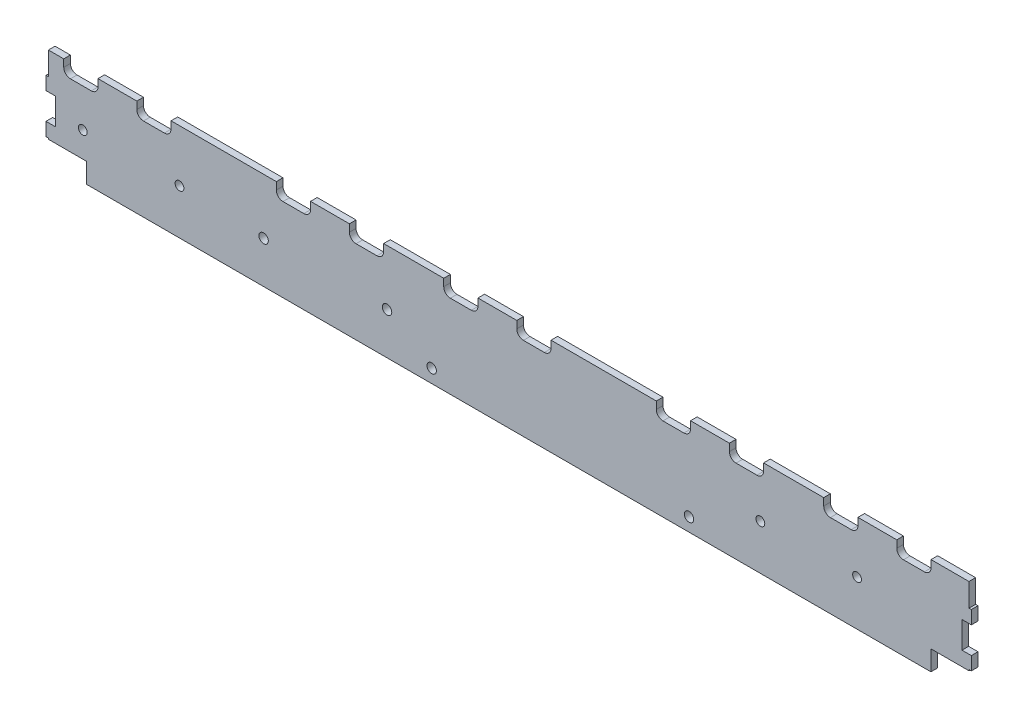
SolidWorks part; units mm, degrees
material "PP Film"
ref_plane "X-Y Datum" through (0, 0, 0) normal (0, 0, 1) x (1, 0, 0)
ref_plane "X-Z Datum" through (0, 0, 0) normal (0, 1, 0) x (1, 0, 0)
ref_plane "Y-Z Datum" through (0, 0, 0) normal (1, 0, 0) x (0, 0, -1)
sketch "Sketch2" plane through (0, 0, 0) normal (0, 0, 1) x (1, 0, 0)
  line L0 (-166.3768, -167.122) -> (-166.3768, -157.216)
  line L1 (-167.5198, -174.615) -> (-167.5198, -187.315)
  line L2 (273.6032, -167.122) -> (273.6032, -157.216)
  line L3 (-163.0588, -174.615) -> (-163.0588, -187.315)
  line L4 (274.7462, -174.615) -> (274.7462, -187.315)
  line L5 (270.2852, -174.615) -> (270.2852, -187.315)
  line L64 (255.4262, -203.714) -> (255.4262, -194.181)
  line L65 (255.4262, -194.181) -> (273.6032, -194.181)
  line L66 (275.7462, -167.122) -> (275.7462, -157.216)
  line L67 (255.4262, -194.181) -> (273.6032, -194.181)
  line L68 (273.6032, -194.181) -> (273.6032, -193.665)
  line L69 (273.6032, -193.665) -> (274.7462, -193.665)
  line L70 (274.7462, -193.665) -> (274.7462, -187.315)
  line L71 (274.7462, -168.265) -> (273.6032, -168.265)
  line L72 (273.6032, -168.265) -> (273.6032, -167.122)
  line L73 (273.6032, -167.122) -> (275.7462, -167.122)
  line L74 (-166.3768, -194.181) -> (-148.1998, -194.181)
  line L75 (275.7462, -157.216) -> (255.4633, -157.216)
  line L76 (255.4633, -157.216) -> (255.4633, -160.708)
  line L77 (252.2883, -163.883) -> (242.2883, -163.883)
  line L78 (239.1133, -160.708) -> (239.1133, -157.216)
  line L79 (239.1133, -157.216) -> (220.5383, -157.216)
  line L80 (220.5383, -157.216) -> (220.5383, -160.708)
  line L81 (217.3633, -163.883) -> (207.3633, -163.883)
  line L82 (204.1883, -160.708) -> (204.1883, -157.216)
  line L83 (204.1883, -157.216) -> (175.4521, -157.216)
  line L84 (175.4521, -157.216) -> (175.4521, -160.708)
  line L85 (172.2771, -163.883) -> (162.2771, -163.883)
  line L86 (159.1021, -160.708) -> (159.1021, -157.216)
  line L87 (159.1021, -157.216) -> (140.5271, -157.216)
  line L88 (140.5271, -157.216) -> (140.5271, -160.708)
  line L89 (137.3521, -163.883) -> (127.3521, -163.883)
  line L90 (124.1771, -160.708) -> (124.1771, -157.216)
  line L91 (124.1771, -157.216) -> (73.8493, -157.216)
  line L92 (73.8493, -157.216) -> (73.8493, -160.708)
  line L93 (70.6743, -163.883) -> (60.6743, -163.883)
  line L94 (57.4993, -160.708) -> (57.4993, -157.216)
  line L95 (57.4993, -157.216) -> (38.9243, -157.216)
  line L96 (38.9243, -157.216) -> (38.9243, -160.708)
  line L97 (35.7493, -163.883) -> (25.7493, -163.883)
  line L98 (22.5743, -160.708) -> (22.5743, -157.216)
  line L99 (22.5743, -157.216) -> (-6.1619, -157.216)
  line L100 (-6.1619, -157.216) -> (-6.1619, -160.708)
  line L101 (-9.3369, -163.883) -> (-19.3369, -163.883)
  line L102 (-22.5119, -160.708) -> (-22.5119, -157.216)
  line L103 (-22.5119, -157.216) -> (-41.0869, -157.216)
  line L104 (-41.0869, -157.216) -> (-41.0869, -160.708)
  line L105 (-44.2619, -163.883) -> (-54.2619, -163.883)
  line L106 (-57.4369, -160.708) -> (-57.4369, -157.216)
  line L107 (-57.4369, -157.216) -> (-107.7647, -157.216)
  line L108 (-107.7647, -157.216) -> (-107.7647, -160.708)
  line L109 (-110.9397, -163.883) -> (-120.9397, -163.883)
  line L110 (-124.1147, -160.708) -> (-124.1147, -157.216)
  line L111 (-124.1147, -157.216) -> (-142.6897, -157.216)
  line L112 (-142.6897, -157.216) -> (-142.6897, -160.708)
  line L113 (-145.8647, -163.883) -> (-155.8647, -163.883)
  line L114 (-159.0397, -160.708) -> (-159.0397, -157.216)
  line L115 (-159.0397, -157.216) -> (-168.5198, -157.216)
  line L116 (-168.5198, -157.216) -> (-168.5198, -167.122)
  line L117 (-168.5198, -167.122) -> (-166.3768, -167.122)
  line L118 (-166.3768, -167.122) -> (-166.3768, -168.265)
  line L119 (-166.3768, -168.265) -> (-167.5198, -168.265)
  line L120 (-167.5198, -168.265) -> (-167.5198, -174.615)
  line L121 (-167.5198, -193.665) -> (-166.3768, -193.665)
  line L122 (-166.3768, -193.665) -> (-166.3768, -194.181)
  line L123 (-166.3768, -194.181) -> (-148.1998, -194.181)
  line L126 (-148.1998, -194.181) -> (-148.1998, -203.714)
  line L127 (-148.1998, -203.714) -> (255.4262, -203.714)
  line L128 (255.4262, -203.714) -> (255.4262, -194.181)
  line L130 (275.7462, -167.122) -> (275.7462, -157.216)
  line L132 (273.6032, -194.181) -> (273.6032, -193.665)
  line L133 (273.6032, -193.665) -> (274.7462, -193.665)
  line L134 (274.7462, -193.665) -> (274.7462, -187.315)
  line L135 (274.7462, -168.265) -> (273.6032, -168.265)
  line L136 (273.6032, -168.265) -> (273.6032, -167.122)
  line L137 (273.6032, -167.122) -> (275.7462, -167.122)
  line L139 (275.7462, -157.216) -> (255.4633, -157.216)
  line L140 (255.4633, -157.216) -> (255.4633, -160.708)
  line L141 (252.2883, -163.883) -> (242.2883, -163.883)
  line L142 (239.1133, -160.708) -> (239.1133, -157.216)
  line L143 (239.1133, -157.216) -> (220.5383, -157.216)
  line L144 (220.5383, -157.216) -> (220.5383, -160.708)
  line L145 (217.3633, -163.883) -> (207.3633, -163.883)
  line L146 (204.1883, -160.708) -> (204.1883, -157.216)
  line L147 (204.1883, -157.216) -> (175.4521, -157.216)
  line L148 (175.4521, -157.216) -> (175.4521, -160.708)
  line L149 (172.2771, -163.883) -> (162.2771, -163.883)
  line L150 (159.1021, -160.708) -> (159.1021, -157.216)
  line L151 (159.1021, -157.216) -> (140.5271, -157.216)
  line L152 (140.5271, -157.216) -> (140.5271, -160.708)
  line L153 (137.3521, -163.883) -> (127.3521, -163.883)
  line L154 (124.1771, -160.708) -> (124.1771, -157.216)
  line L155 (124.1771, -157.216) -> (73.8493, -157.216)
  line L156 (73.8493, -157.216) -> (73.8493, -160.708)
  line L157 (70.6743, -163.883) -> (60.6743, -163.883)
  line L158 (57.4993, -160.708) -> (57.4993, -157.216)
  line L159 (57.4993, -157.216) -> (38.9243, -157.216)
  line L160 (38.9243, -157.216) -> (38.9243, -160.708)
  line L161 (35.7493, -163.883) -> (25.7493, -163.883)
  line L162 (22.5743, -160.708) -> (22.5743, -157.216)
  line L163 (22.5743, -157.216) -> (-6.1619, -157.216)
  line L164 (-6.1619, -157.216) -> (-6.1619, -160.708)
  line L165 (-9.3369, -163.883) -> (-19.3369, -163.883)
  line L166 (-22.5119, -160.708) -> (-22.5119, -157.216)
  line L167 (-22.5119, -157.216) -> (-41.0869, -157.216)
  line L168 (-41.0869, -157.216) -> (-41.0869, -160.708)
  line L169 (-44.2619, -163.883) -> (-54.2619, -163.883)
  line L170 (-57.4369, -160.708) -> (-57.4369, -157.216)
  line L171 (-57.4369, -157.216) -> (-107.7647, -157.216)
  line L172 (-107.7647, -157.216) -> (-107.7647, -160.708)
  line L173 (-110.9397, -163.883) -> (-120.9397, -163.883)
  line L174 (-124.1147, -160.708) -> (-124.1147, -157.216)
  line L175 (-124.1147, -157.216) -> (-142.6897, -157.216)
  line L176 (-142.6897, -157.216) -> (-142.6897, -160.708)
  line L177 (-145.8647, -163.883) -> (-155.8647, -163.883)
  line L178 (-159.0397, -160.708) -> (-159.0397, -157.216)
  line L179 (-159.0397, -157.216) -> (-168.5198, -157.216)
  line L180 (-168.5198, -157.216) -> (-168.5198, -167.122)
  line L181 (-168.5198, -167.122) -> (-166.3768, -167.122)
  line L182 (-166.3768, -167.122) -> (-166.3768, -168.265)
  line L183 (-166.3768, -168.265) -> (-167.5198, -168.265)
  line L184 (-167.5198, -168.265) -> (-167.5198, -174.615)
  line L185 (-167.5198, -193.665) -> (-166.3768, -193.665)
  line L186 (-166.3768, -193.665) -> (-166.3768, -194.181)
  line L190 (-148.1998, -194.181) -> (-148.1998, -203.714)
  line L191 (-148.1998, -203.714) -> (255.4262, -203.714)
  line L249 (255.4262, -194.181) -> (273.6032, -194.181)
  line L250 (273.6032, -194.181) -> (273.6032, -193.665)
  line L251 (273.6032, -193.665) -> (274.7462, -193.665)
  line L252 (274.7462, -193.665) -> (274.7462, -187.315)
  line L253 (274.7462, -168.265) -> (273.6032, -168.265)
  line L254 (273.6032, -168.265) -> (273.6032, -167.122)
  line L255 (273.6032, -167.122) -> (275.7462, -167.122)
  line L256 (275.7462, -167.122) -> (275.7462, -157.216)
  line L257 (275.7462, -157.216) -> (255.4633, -157.216)
  line L258 (255.4633, -157.216) -> (255.4633, -160.708)
  line L259 (252.2883, -163.883) -> (242.2883, -163.883)
  line L260 (239.1133, -160.708) -> (239.1133, -157.216)
  line L261 (239.1133, -157.216) -> (220.5383, -157.216)
  line L262 (220.5383, -157.216) -> (220.5383, -160.708)
  line L263 (217.3633, -163.883) -> (207.3633, -163.883)
  line L264 (204.1883, -160.708) -> (204.1883, -157.216)
  line L265 (204.1883, -157.216) -> (175.4521, -157.216)
  line L266 (175.4521, -157.216) -> (175.4521, -160.708)
  line L267 (172.2771, -163.883) -> (162.2771, -163.883)
  line L268 (159.1021, -160.708) -> (159.1021, -157.216)
  line L269 (159.1021, -157.216) -> (140.5271, -157.216)
  line L270 (140.5271, -157.216) -> (140.5271, -160.708)
  line L271 (137.3521, -163.883) -> (127.3521, -163.883)
  line L272 (124.1771, -160.708) -> (124.1771, -157.216)
  line L273 (124.1771, -157.216) -> (73.8493, -157.216)
  line L274 (73.8493, -157.216) -> (73.8493, -160.708)
  line L275 (70.6743, -163.883) -> (60.6743, -163.883)
  line L276 (57.4993, -160.708) -> (57.4993, -157.216)
  line L277 (57.4993, -157.216) -> (38.9243, -157.216)
  line L278 (38.9243, -157.216) -> (38.9243, -160.708)
  line L279 (35.7493, -163.883) -> (25.7493, -163.883)
  line L280 (22.5743, -160.708) -> (22.5743, -157.216)
  line L281 (22.5743, -157.216) -> (-6.1619, -157.216)
  line L282 (-6.1619, -157.216) -> (-6.1619, -160.708)
  line L283 (-9.3369, -163.883) -> (-19.3369, -163.883)
  line L284 (-22.5119, -160.708) -> (-22.5119, -157.216)
  line L285 (-22.5119, -157.216) -> (-41.0869, -157.216)
  line L286 (-41.0869, -157.216) -> (-41.0869, -160.708)
  line L287 (-44.2619, -163.883) -> (-54.2619, -163.883)
  line L288 (-57.4369, -160.708) -> (-57.4369, -157.216)
  line L289 (-57.4369, -157.216) -> (-107.7647, -157.216)
  line L290 (-107.7647, -157.216) -> (-107.7647, -160.708)
  line L291 (-110.9397, -163.883) -> (-120.9397, -163.883)
  line L292 (-124.1147, -160.708) -> (-124.1147, -157.216)
  line L293 (-124.1147, -157.216) -> (-142.6897, -157.216)
  line L294 (-142.6897, -157.216) -> (-142.6897, -160.708)
  line L295 (-145.8647, -163.883) -> (-155.8647, -163.883)
  line L296 (-159.0397, -160.708) -> (-159.0397, -157.216)
  line L297 (-159.0397, -157.216) -> (-168.5198, -157.216)
  line L298 (-168.5198, -157.216) -> (-168.5198, -167.122)
  line L299 (-168.5198, -167.122) -> (-166.3768, -167.122)
  line L300 (-166.3768, -167.122) -> (-166.3768, -168.265)
  line L301 (-166.3768, -168.265) -> (-167.5198, -168.265)
  line L302 (-167.5198, -168.265) -> (-167.5198, -174.615)
  line L303 (-167.5198, -193.665) -> (-166.3768, -193.665)
  line L304 (-166.3768, -193.665) -> (-166.3768, -194.181)
  line L305 (-166.3768, -194.181) -> (-148.1998, -194.181)
  line L306 (-148.1998, -194.181) -> (-148.1998, -203.714)
  line L307 (-148.1998, -203.714) -> (255.4262, -203.714)
  line L308 (255.4262, -203.714) -> (255.4262, -194.181)
  line L309 (255.4262, -194.181) -> (273.6032, -194.181)
  line L310 (273.6032, -194.181) -> (273.6032, -193.665)
  line L311 (273.6032, -193.665) -> (274.7462, -193.665)
  line L312 (274.7462, -193.665) -> (274.7462, -187.315)
  line L313 (274.7462, -168.265) -> (273.6032, -168.265)
  line L314 (273.6032, -168.265) -> (273.6032, -167.122)
  line L315 (273.6032, -167.122) -> (275.7462, -167.122)
  line L316 (275.7462, -167.122) -> (275.7462, -157.216)
  line L317 (275.7462, -157.216) -> (255.4633, -157.216)
  line L318 (255.4633, -157.216) -> (255.4633, -160.708)
  line L319 (252.2883, -163.883) -> (242.2883, -163.883)
  line L320 (239.1133, -160.708) -> (239.1133, -157.216)
  line L321 (239.1133, -157.216) -> (220.5383, -157.216)
  line L322 (220.5383, -157.216) -> (220.5383, -160.708)
  line L323 (217.3633, -163.883) -> (207.3633, -163.883)
  line L324 (204.1883, -160.708) -> (204.1883, -157.216)
  line L325 (204.1883, -157.216) -> (175.4521, -157.216)
  line L326 (175.4521, -157.216) -> (175.4521, -160.708)
  line L327 (172.2771, -163.883) -> (162.2771, -163.883)
  line L328 (159.1021, -160.708) -> (159.1021, -157.216)
  line L329 (159.1021, -157.216) -> (140.5271, -157.216)
  line L330 (140.5271, -157.216) -> (140.5271, -160.708)
  line L331 (137.3521, -163.883) -> (127.3521, -163.883)
  line L332 (124.1771, -160.708) -> (124.1771, -157.216)
  line L333 (124.1771, -157.216) -> (73.8493, -157.216)
  line L334 (73.8493, -157.216) -> (73.8493, -160.708)
  line L335 (70.6743, -163.883) -> (60.6743, -163.883)
  line L336 (57.4993, -160.708) -> (57.4993, -157.216)
  line L337 (57.4993, -157.216) -> (38.9243, -157.216)
  line L338 (38.9243, -157.216) -> (38.9243, -160.708)
  line L339 (35.7493, -163.883) -> (25.7493, -163.883)
  line L340 (22.5743, -160.708) -> (22.5743, -157.216)
  line L341 (22.5743, -157.216) -> (-6.1619, -157.216)
  line L342 (-6.1619, -157.216) -> (-6.1619, -160.708)
  line L343 (-9.3369, -163.883) -> (-19.3369, -163.883)
  line L344 (-22.5119, -160.708) -> (-22.5119, -157.216)
  line L345 (-22.5119, -157.216) -> (-41.0869, -157.216)
  line L346 (-41.0869, -157.216) -> (-41.0869, -160.708)
  line L347 (-44.2619, -163.883) -> (-54.2619, -163.883)
  line L348 (-57.4369, -160.708) -> (-57.4369, -157.216)
  line L349 (-57.4369, -157.216) -> (-107.7647, -157.216)
  line L350 (-107.7647, -157.216) -> (-107.7647, -160.708)
  line L351 (-110.9397, -163.883) -> (-120.9397, -163.883)
  line L352 (-124.1147, -160.708) -> (-124.1147, -157.216)
  line L353 (-124.1147, -157.216) -> (-142.6897, -157.216)
  line L354 (-142.6897, -157.216) -> (-142.6897, -160.708)
  line L355 (-145.8647, -163.883) -> (-155.8647, -163.883)
  line L356 (-159.0397, -160.708) -> (-159.0397, -157.216)
  line L357 (-159.0397, -157.216) -> (-168.5198, -157.216)
  line L358 (-168.5198, -157.216) -> (-168.5198, -167.122)
  line L359 (-168.5198, -167.122) -> (-166.3768, -167.122)
  line L360 (-166.3768, -167.122) -> (-166.3768, -168.265)
  line L361 (-166.3768, -168.265) -> (-167.5198, -168.265)
  line L362 (-167.5198, -168.265) -> (-167.5198, -174.615)
  line L363 (-167.5198, -193.665) -> (-166.3768, -193.665)
  line L364 (-166.3768, -193.665) -> (-166.3768, -194.181)
  line L365 (-166.3768, -194.181) -> (-148.1998, -194.181)
  line L366 (-148.1998, -194.181) -> (-148.1998, -203.714)
  line L367 (-148.1998, -203.714) -> (255.4262, -203.714)
  line L368 (255.4262, -203.714) -> (255.4262, -194.181)
  line L384 (270.2852, -174.615) -> (274.7462, -174.615)
  line L385 (270.2852, -174.615) -> (274.7462, -174.615)
  line L386 (274.7462, -174.615) -> (274.7462, -168.265)
  line L387 (274.7462, -174.615) -> (274.7462, -168.265)
  line L388 (-167.5198, -174.615) -> (-163.0588, -174.615)
  line L389 (-167.5198, -174.615) -> (-163.0588, -174.615)
  line L390 (-159.8838, -177.79) -> (-159.8838, -184.14)
  line L392 (-163.0588, -187.315) -> (-167.5198, -187.315)
  line L393 (-163.0588, -187.315) -> (-167.5198, -187.315)
  line L394 (-167.5198, -187.315) -> (-167.5198, -193.665)
  line L395 (-167.5198, -187.315) -> (-167.5198, -193.665)
  line L396 (274.7462, -187.315) -> (270.2852, -187.315)
  line L397 (274.7462, -187.315) -> (270.2852, -187.315)
  line L398 (267.1102, -184.14) -> (267.1102, -177.79)
  line L400 (270.2852, -174.615) -> (274.7462, -174.615)
  line L401 (270.2852, -174.615) -> (274.7462, -174.615)
  line L402 (274.7462, -174.615) -> (274.7462, -168.265)
  line L403 (274.7462, -174.615) -> (274.7462, -168.265)
  line L404 (-167.5198, -174.615) -> (-163.0588, -174.615)
  line L405 (-167.5198, -174.615) -> (-163.0588, -174.615)
  line L406 (-159.8838, -177.79) -> (-159.8838, -184.14)
  line L408 (-163.0588, -187.315) -> (-167.5198, -187.315)
  line L409 (-163.0588, -187.315) -> (-167.5198, -187.315)
  line L410 (-167.5198, -187.315) -> (-167.5198, -193.665)
  line L411 (-167.5198, -187.315) -> (-167.5198, -193.665)
  line L412 (274.7462, -187.315) -> (270.2852, -187.315)
  line L413 (274.7462, -187.315) -> (270.2852, -187.315)
  line L414 (267.1102, -184.14) -> (267.1102, -177.79)
  arc A20 (252.2883, -163.883) -> (255.4633, -160.708) centre (252.2883, -160.708) ccw
  arc A21 (239.1133, -160.708) -> (242.2883, -163.883) centre (242.2883, -160.708) ccw
  arc A22 (217.3633, -163.883) -> (220.5383, -160.708) centre (217.3633, -160.708) ccw
  arc A23 (204.1883, -160.708) -> (207.3633, -163.883) centre (207.3633, -160.708) ccw
  arc A24 (172.2771, -163.883) -> (175.4521, -160.708) centre (172.2771, -160.708) ccw
  arc A25 (159.1021, -160.708) -> (162.2771, -163.883) centre (162.2771, -160.708) ccw
  arc A26 (137.3521, -163.883) -> (140.5271, -160.708) centre (137.3521, -160.708) ccw
  arc A27 (124.1771, -160.708) -> (127.3521, -163.883) centre (127.3521, -160.708) ccw
  arc A28 (70.6743, -163.883) -> (73.8493, -160.708) centre (70.6743, -160.708) ccw
  arc A29 (57.4993, -160.708) -> (60.6743, -163.883) centre (60.6743, -160.708) ccw
  arc A30 (35.7493, -163.883) -> (38.9243, -160.708) centre (35.7493, -160.708) ccw
  arc A31 (22.5743, -160.708) -> (25.7493, -163.883) centre (25.7493, -160.708) ccw
  arc A32 (-9.3369, -163.883) -> (-6.1619, -160.708) centre (-9.3369, -160.708) ccw
  arc A33 (-22.5119, -160.708) -> (-19.3369, -163.883) centre (-19.3369, -160.708) ccw
  arc A34 (-44.2619, -163.883) -> (-41.0869, -160.708) centre (-44.2619, -160.708) ccw
  arc A35 (-57.4369, -160.708) -> (-54.2619, -163.883) centre (-54.2619, -160.708) ccw
  arc A36 (-110.9397, -163.883) -> (-107.7647, -160.708) centre (-110.9397, -160.708) ccw
  arc A37 (-124.1147, -160.708) -> (-120.9397, -163.883) centre (-120.9397, -160.708) ccw
  arc A38 (-145.8647, -163.883) -> (-142.6897, -160.708) centre (-145.8647, -160.708) ccw
  arc A39 (-159.0397, -160.708) -> (-155.8647, -163.883) centre (-155.8647, -160.708) ccw
  arc A40 (252.2883, -163.883) -> (255.4633, -160.708) centre (252.2883, -160.708) ccw
  arc A41 (239.1133, -160.708) -> (242.2883, -163.883) centre (242.2883, -160.708) ccw
  arc A42 (217.3633, -163.883) -> (220.5383, -160.708) centre (217.3633, -160.708) ccw
  arc A43 (204.1883, -160.708) -> (207.3633, -163.883) centre (207.3633, -160.708) ccw
  arc A44 (172.2771, -163.883) -> (175.4521, -160.708) centre (172.2771, -160.708) ccw
  arc A45 (159.1021, -160.708) -> (162.2771, -163.883) centre (162.2771, -160.708) ccw
  arc A46 (137.3521, -163.883) -> (140.5271, -160.708) centre (137.3521, -160.708) ccw
  arc A47 (124.1771, -160.708) -> (127.3521, -163.883) centre (127.3521, -160.708) ccw
  arc A48 (70.6743, -163.883) -> (73.8493, -160.708) centre (70.6743, -160.708) ccw
  arc A49 (57.4993, -160.708) -> (60.6743, -163.883) centre (60.6743, -160.708) ccw
  arc A50 (35.7493, -163.883) -> (38.9243, -160.708) centre (35.7493, -160.708) ccw
  arc A51 (22.5743, -160.708) -> (25.7493, -163.883) centre (25.7493, -160.708) ccw
  arc A52 (-9.3369, -163.883) -> (-6.1619, -160.708) centre (-9.3369, -160.708) ccw
  arc A53 (-22.5119, -160.708) -> (-19.3369, -163.883) centre (-19.3369, -160.708) ccw
  arc A54 (-44.2619, -163.883) -> (-41.0869, -160.708) centre (-44.2619, -160.708) ccw
  arc A55 (-57.4369, -160.708) -> (-54.2619, -163.883) centre (-54.2619, -160.708) ccw
  arc A56 (-110.9397, -163.883) -> (-107.7647, -160.708) centre (-110.9397, -160.708) ccw
  arc A57 (-124.1147, -160.708) -> (-120.9397, -163.883) centre (-120.9397, -160.708) ccw
  arc A58 (-145.8647, -163.883) -> (-142.6897, -160.708) centre (-145.8647, -160.708) ccw
  arc A59 (-159.0397, -160.708) -> (-155.8647, -163.883) centre (-155.8647, -160.708) ccw
  arc A80 (252.2883, -163.883) -> (255.4633, -160.708) centre (252.2883, -160.708) ccw
  arc A81 (239.1133, -160.708) -> (242.2883, -163.883) centre (242.2883, -160.708) ccw
  arc A82 (217.3633, -163.883) -> (220.5383, -160.708) centre (217.3633, -160.708) ccw
  arc A83 (204.1883, -160.708) -> (207.3633, -163.883) centre (207.3633, -160.708) ccw
  arc A84 (172.2771, -163.883) -> (175.4521, -160.708) centre (172.2771, -160.708) ccw
  arc A85 (159.1021, -160.708) -> (162.2771, -163.883) centre (162.2771, -160.708) ccw
  arc A86 (137.3521, -163.883) -> (140.5271, -160.708) centre (137.3521, -160.708) ccw
  arc A87 (124.1771, -160.708) -> (127.3521, -163.883) centre (127.3521, -160.708) ccw
  arc A88 (70.6743, -163.883) -> (73.8493, -160.708) centre (70.6743, -160.708) ccw
  arc A89 (57.4993, -160.708) -> (60.6743, -163.883) centre (60.6743, -160.708) ccw
  arc A90 (35.7493, -163.883) -> (38.9243, -160.708) centre (35.7493, -160.708) ccw
  arc A91 (22.5743, -160.708) -> (25.7493, -163.883) centre (25.7493, -160.708) ccw
  arc A92 (-9.3369, -163.883) -> (-6.1619, -160.708) centre (-9.3369, -160.708) ccw
  arc A93 (-22.5119, -160.708) -> (-19.3369, -163.883) centre (-19.3369, -160.708) ccw
  arc A94 (-44.2619, -163.883) -> (-41.0869, -160.708) centre (-44.2619, -160.708) ccw
  arc A95 (-57.4369, -160.708) -> (-54.2619, -163.883) centre (-54.2619, -160.708) ccw
  arc A96 (-110.9397, -163.883) -> (-107.7647, -160.708) centre (-110.9397, -160.708) ccw
  arc A97 (-124.1147, -160.708) -> (-120.9397, -163.883) centre (-120.9397, -160.708) ccw
  arc A98 (-145.8647, -163.883) -> (-142.6897, -160.708) centre (-145.8647, -160.708) ccw
  arc A99 (-159.0397, -160.708) -> (-155.8647, -163.883) centre (-155.8647, -160.708) ccw
  arc A100 (252.2883, -163.883) -> (255.4633, -160.708) centre (252.2883, -160.708) ccw
  arc A101 (239.1133, -160.708) -> (242.2883, -163.883) centre (242.2883, -160.708) ccw
  arc A102 (217.3633, -163.883) -> (220.5383, -160.708) centre (217.3633, -160.708) ccw
  arc A103 (204.1883, -160.708) -> (207.3633, -163.883) centre (207.3633, -160.708) ccw
  arc A104 (172.2771, -163.883) -> (175.4521, -160.708) centre (172.2771, -160.708) ccw
  arc A105 (159.1021, -160.708) -> (162.2771, -163.883) centre (162.2771, -160.708) ccw
  arc A106 (137.3521, -163.883) -> (140.5271, -160.708) centre (137.3521, -160.708) ccw
  arc A107 (124.1771, -160.708) -> (127.3521, -163.883) centre (127.3521, -160.708) ccw
  arc A108 (70.6743, -163.883) -> (73.8493, -160.708) centre (70.6743, -160.708) ccw
  arc A109 (57.4993, -160.708) -> (60.6743, -163.883) centre (60.6743, -160.708) ccw
  arc A110 (35.7493, -163.883) -> (38.9243, -160.708) centre (35.7493, -160.708) ccw
  arc A111 (22.5743, -160.708) -> (25.7493, -163.883) centre (25.7493, -160.708) ccw
  arc A112 (-9.3369, -163.883) -> (-6.1619, -160.708) centre (-9.3369, -160.708) ccw
  arc A113 (-22.5119, -160.708) -> (-19.3369, -163.883) centre (-19.3369, -160.708) ccw
  arc A114 (-44.2619, -163.883) -> (-41.0869, -160.708) centre (-44.2619, -160.708) ccw
  arc A115 (-57.4369, -160.708) -> (-54.2619, -163.883) centre (-54.2619, -160.708) ccw
  arc A116 (-110.9397, -163.883) -> (-107.7647, -160.708) centre (-110.9397, -160.708) ccw
  arc A117 (-124.1147, -160.708) -> (-120.9397, -163.883) centre (-120.9397, -160.708) ccw
  arc A118 (-145.8647, -163.883) -> (-142.6897, -160.708) centre (-145.8647, -160.708) ccw
  arc A119 (-159.0397, -160.708) -> (-155.8647, -163.883) centre (-155.8647, -160.708) ccw
  arc A128 (270.2852, -174.615) -> (267.1102, -177.79) centre (270.2852, -177.79) ccw
  arc A130 (-159.8838, -177.79) -> (-163.0588, -174.615) centre (-163.0588, -177.79) ccw
  arc A132 (-163.0588, -187.315) -> (-159.8838, -184.14) centre (-163.0588, -184.14) ccw
  arc A134 (267.1102, -184.14) -> (270.2852, -187.315) centre (270.2852, -184.14) ccw
  arc A136 (270.2852, -174.615) -> (267.1102, -177.79) centre (270.2852, -177.79) ccw
  arc A138 (-159.8838, -177.79) -> (-163.0588, -174.615) centre (-163.0588, -177.79) ccw
  arc A140 (-163.0588, -187.315) -> (-159.8838, -184.14) centre (-163.0588, -184.14) ccw
  arc A142 (267.1102, -184.14) -> (270.2852, -187.315) centre (270.2852, -184.14) ccw
  dimension "D1" = 0
  dimension "D2" = 0
extrude "Boss-Extrude1" add sketch "Sketch2" along normal blind 3.175
sketch "Sketch4" plane through (0, 0, 3.175) normal (0, 0, 1) x (1, 0, 0)
  circle A0 centre (220.1062, -182.1047) radius 2.1 construction
  circle A1 centre (173.9062, -182.1047) radius 2.1 construction
  circle A2 centre (139.8181, -197.3292) radius 2.25 construction
  circle A3 centre (16.8181, -197.3292) radius 2.25 construction
  circle A4 centre (-4.5198, -183.714) radius 2.25 construction
  circle A5 centre (-63.5198, -183.714) radius 2.25 construction
  circle A6 centre (-103.7233, -182.1047) radius 2.1 construction
  circle A7 centre (-149.9233, -182.1047) radius 2.1 construction
  circle A8 centre (220.1062, -182.1047) radius 2.1
  circle A9 centre (173.9062, -182.1047) radius 2.1
  circle A10 centre (139.8181, -197.3292) radius 2.25
  circle A11 centre (16.8181, -197.3292) radius 2.25
  circle A12 centre (-4.5198, -183.714) radius 2.25
  circle A13 centre (-63.5198, -183.714) radius 2.25
  circle A14 centre (-103.7233, -182.1047) radius 2.1
  circle A15 centre (-149.9233, -182.1047) radius 2.1
extrude "Cut-Extrude2" cut sketch "Sketch4" against normal through all
